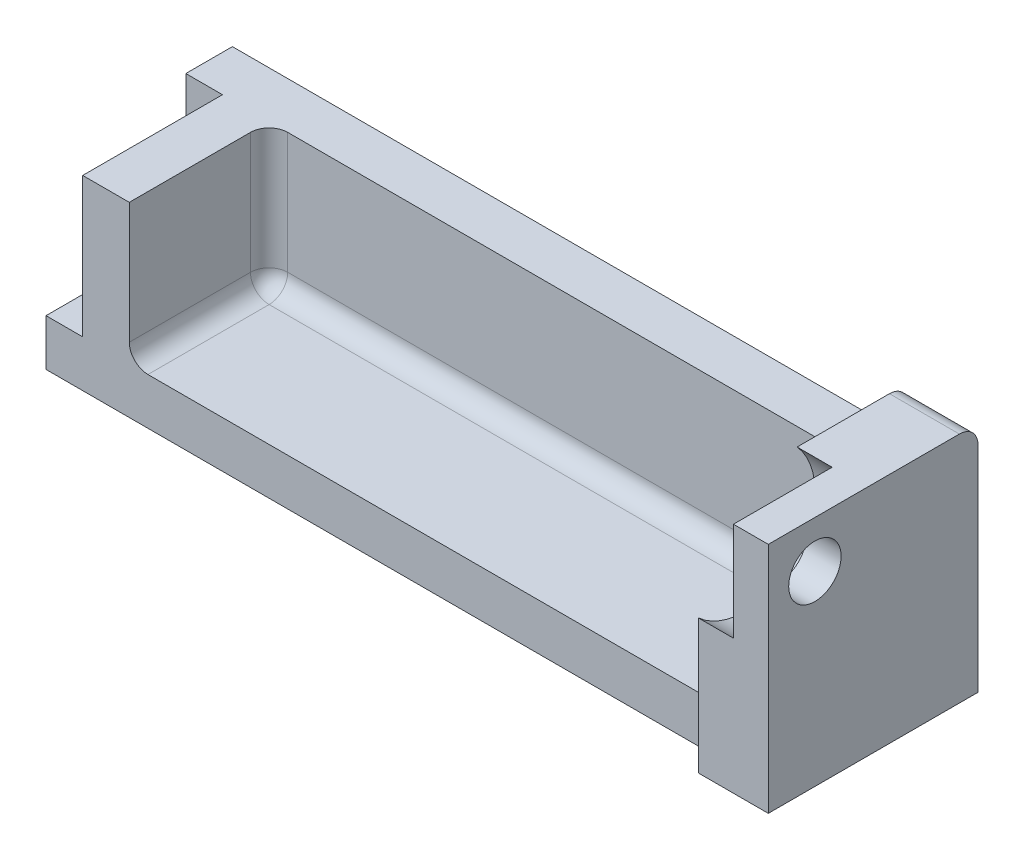
SolidWorks part; units mm, degrees
ref_plane "Front Plane" through (0, 0, 0) normal (0, 0, 1) x (1, 0, 0)
ref_plane "Top Plane" through (0, 0, 0) normal (0, 1, 0) x (1, 0, 0)
ref_plane "Right Plane" through (0, 0, 0) normal (1, 0, 0) x (0, 0, -1)
sketch "Sketch1" plane through (0, 0, 0) normal (0, 0, 1) x (1, 0, 0)
  line L1 (-66.8759, 63.2321) -> (34.7241, 63.2321)
  line L2 (-66.8759, 63.2321) -> (-66.8759, 37.8321)
  line L3 (-66.8759, 37.8321) -> (34.7241, 37.8321)
  line L4 (34.7241, 63.2321) -> (34.7241, 37.8321)
  dimension "D1" = 101.6
  dimension "D2" = 25.4
extrude "Boss-Extrude1" add sketch "Sketch1" along normal blind 25.4
sketch "Sketch2" plane through (0, 63.2321, 0) normal (0, 1, 0) x (1, 0, 0)
  line L0 (34.7241, -25.4) -> (-66.8759, -25.4) construction
  line L1 (-55.5259, -25.4) -> (25.1991, -25.4)
  line L2 (-55.5259, -25.4) -> (-55.5259, -6.35)
  line L3 (-55.5259, -6.35) -> (25.1991, -6.35)
  line L4 (25.1991, -25.4) -> (25.1991, -6.35)
  line L5 (-66.8759, -25.4) -> (-66.8759, 0) construction
  line L6 (34.7241, -25.4) -> (34.7241, 0) construction
  line L7 (34.7241, 0) -> (-66.8759, 0) construction
  dimension "D1" = 11.35
  dimension "D2" = 9.525
  dimension "D3" = 6.35
extrude "Cut-Extrude1" cut sketch "Sketch2" against normal blind 19.05
sketch "Sketch3" plane through (-66.8759, 0, 0) normal (-1, 0, 0) x (0, 0, 1)
  line L0 (0, 63.2321) -> (0, 37.8321) construction
  line L1 (25.4, 63.2321) -> (6.35, 63.2321)
  line L2 (25.4, 63.2321) -> (25.4, 44.1821)
  line L3 (25.4, 44.1821) -> (6.35, 44.1821)
  line L4 (6.35, 63.2321) -> (6.35, 44.1821)
  line L5 (25.4, 37.8321) -> (0, 37.8321) construction
  dimension "D1" = 6.35
  dimension "D2" = 6.35
extrude "Cut-Extrude2" cut sketch "Sketch3" against normal blind 5
sketch "Sketch4" plane through (0, 0, 25.4) normal (0, 0, 1) x (1, 0, 0)
  line L1 (25.1991, 63.2321) -> (34.7241, 63.2321)
  line L2 (25.1991, 63.2321) -> (25.1991, 37.8321)
  line L3 (25.1991, 37.8321) -> (34.7241, 37.8321)
  line L4 (34.7241, 63.2321) -> (34.7241, 37.8321)
extrude "Boss-Extrude2" add sketch "Sketch4" along normal blind 3.175
sketch "Sketch8" plane through (0, 63.2321, 0) normal (0, 1, 0) x (1, 0, 0)
  line L1 (34.7241, 0) -> (25.1991, 0)
  line L2 (34.7241, 0) -> (34.7241, -28.575)
  line L3 (34.7241, -28.575) -> (25.1991, -28.575)
  line L4 (25.1991, 0) -> (25.1991, -28.575)
extrude "Boss-Extrude3" add sketch "Sketch8" along normal blind 6.35
sketch "Sketch5" plane through (25.1991, 0, 0) normal (-1, 0, 0) x (0, 0, 1)
  line L0 (28.575, 69.5821) -> (28.575, 37.8321) construction
  line L6 (0, 69.5821) -> (28.575, 69.5821) construction
  point P0 (22.225, 63.2321)
  dimension "D1" = 6.35
  dimension "D2" = 6.35
hole_wizard "CBORE for 1/4 Hex Head Bolt1" positions "Sketch6" profile "Sketch7" counterbore size "1/4" standard "ANSI Inch"
sketch "Sketch6" plane through (25.1991, 0, 0) normal (-1, 0, 0) x (0, 0, 1)
  point P0 (22.225, 63.2321)
sketch "Sketch7" plane through (25.1991, 63.2321, 22.225) normal (0, 1, 0) x (0, 0, 1)
  line L0 (0, 0) -> (0, 12.0518)
  line L1 (0, 12.0518) -> (3.5712, 9.906)
  line L2 (3.5712, 9.906) -> (3.5712, 4.7752)
  line L3 (3.5712, 4.7752) -> (9.525, 4.7752)
  line L4 (9.525, 4.7752) -> (9.525, 0)
  line L5 (9.525, 0) -> (0, 0)
  line L10 (0, 12.0518) -> (-3.5712, 9.906) construction
  line L11 (0, -6.35) -> (0, 107.95) construction
  dimension "Hole Dia." = 7.1425
  dimension "Hole Depth" = 9.906
  dimension "C'Bore Dia." = 19.05
  dimension "C'Bore Depth" = 4.7752
  dimension "Drill Angle" = 118
fillet "Fillet1" radius 2.54 8 edges at (-55.5259, 53.7071, 6.35) (-55.5259, 44.1821, 15.875) (-15.1634, 44.1821, 6.35) (25.1991, 53.7071, 6.35) (25.1991, 44.1821, 15.875) (25.1991, 41.0071, 25.4) (29.9616, 69.5821, 0) (25.1991, 63.2321, 3.175)
equation "\"height\"=4"
equation "\"D1@Sketch1\"=\"height\""
equation "\"traythickness\"= 5 / 25.4"
equation "\"D1@Sketch2\"= 0.25in + \"traythickness\""
equation "\"D1@Cut-Extrude2\"= \"traythickness\""
